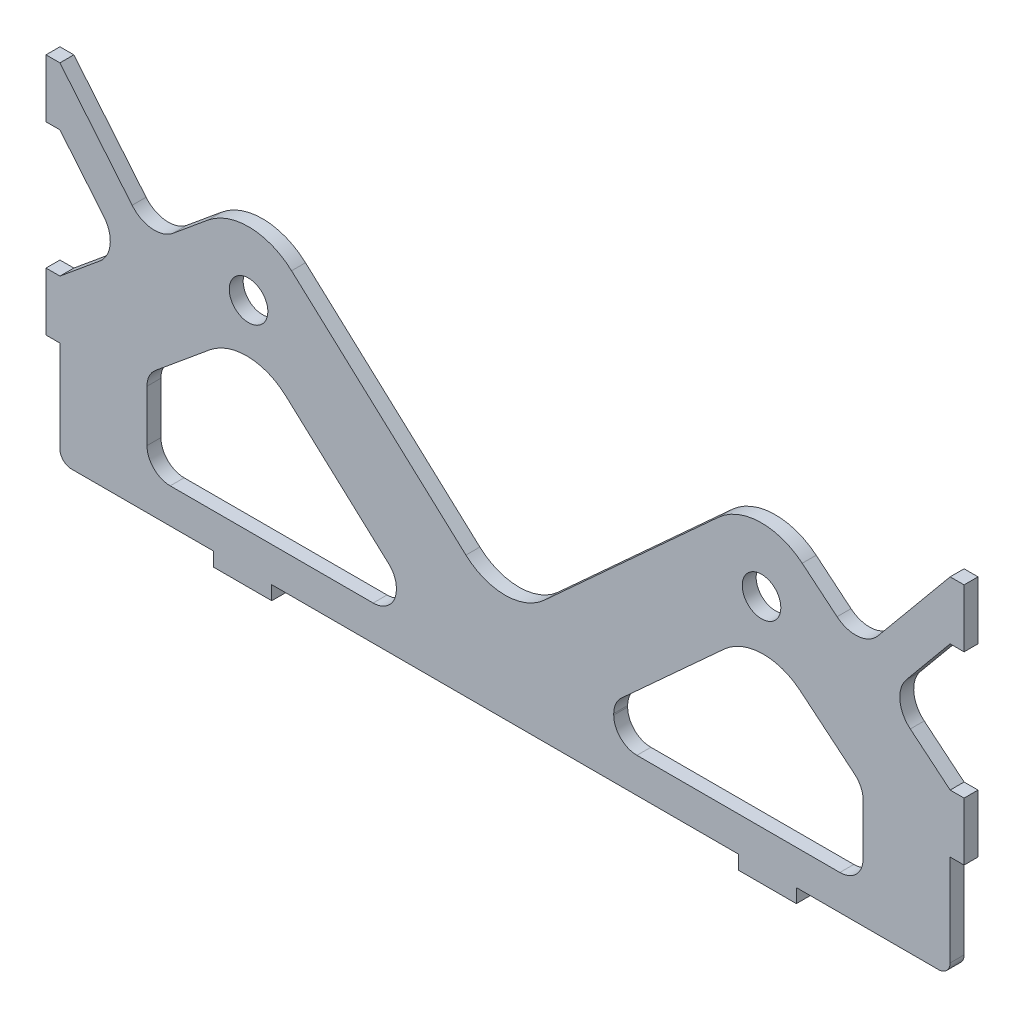
SolidWorks part; units mm, degrees
material "AISI 1020"
ref_plane "Front Plane" through (0, 0, 0) normal (0, 0, 1) x (1, 0, 0)
ref_plane "Top Plane" through (0, 0, 0) normal (0, 1, 0) x (1, 0, 0)
ref_plane "Right Plane" through (0, 0, 0) normal (1, 0, 0) x (0, 0, -1)
sketch "Sketch1" plane through (0, 0, 0) normal (0, 0, 1) x (1, 0, 0)
  line L1 (-97.4016, 35.56) -> (-97.4016, 62.7603) construction
  line L5 (51.054, 0) -> (-51.054, 0)
  line L6 (-51.054, 0) -> (-51.054, -3.048)
  line L7 (-51.054, -3.048) -> (-63.754, -3.048)
  line L8 (-63.754, -3.048) -> (-63.754, 0)
  line L9 (-63.754, 0) -> (-94.8616, 0)
  line L10 (-97.4016, 2.54) -> (-97.4016, 22.606)
  line L11 (-97.4016, 22.606) -> (-100.4496, 22.606)
  line L12 (-100.4496, 22.606) -> (-100.4496, 35.306)
  line L13 (-100.4496, 35.306) -> (-97.4016, 35.306)
  line L15 (-100.4496, 35.56) -> (-100.4496, 62.7603) construction
  line L16 (-64.008, -3.048) -> (-94.7346, -3.048) construction
  line L17 (-97.4016, 35.306) -> (-65.0347, 62.0991)
  line L18 (-46.712, 61.6589) -> (0, 19.05)
  line L19 (-100.4496, 35.56) -> (-97.4016, 35.56) construction
  line L20 (-50.8, -3.048) -> (-50.8, 0) construction
  line L21 (-97.4016, 2.667) -> (-97.4016, 22.352) construction
  line L22 (0, -1000) -> (0, 49000) construction
  line L23 (46.712, 61.6589) -> (0, 19.05)
  line L24 (97.4016, 35.306) -> (65.0347, 62.0991)
  line L25 (100.4496, 35.306) -> (97.4016, 35.306)
  line L26 (100.4496, 22.606) -> (100.4496, 35.306)
  line L27 (97.4016, 22.606) -> (100.4496, 22.606)
  line L28 (97.4016, 2.54) -> (97.4016, 22.606)
  line L29 (63.754, 0) -> (94.8616, 0)
  line L30 (63.754, -3.048) -> (63.754, 0)
  line L31 (51.054, -3.048) -> (63.754, -3.048)
  line L32 (51.054, 0) -> (51.054, -3.048)
  arc A0 (-46.712, 61.6589) -> (-65.0347, 62.0991) centre (-56.1266, 51.3377) ccw
  arc A1 (-94.8616, 0) -> (-97.4016, 2.54) centre (-94.8616, 2.54) cw
  circle A2 centre (56.1266, 51.3377) radius 4.2227
  circle A3 centre (-56.1266, 51.3377) radius 4.2227
  circle A4 centre (-56.1266, 51.3377) radius 4.2227
  arc A5 (94.8616, 0) -> (97.4016, 2.54) centre (94.8616, 2.54) ccw
  arc A6 (46.712, 61.6589) -> (65.0347, 62.0991) centre (56.1266, 51.3377) cw
  point P52 (0, 0)
  dimension "D2" = 27.94
  dimension "D7" = 2.54
  dimension "D1" = 12.7
  dimension "D4" = 19.05
  dimension "D5" = 0.254
  dimension "D6" = 0.254
  dimension "D3" = 0.254
extrude "Boss-Extrude1" add sketch "Sketch1" against normal blind 3.048 contours A2 | A4 | L17 A0 L18 L23 A6 L24 L25 L26 L27 L28 A5 L29 L30 L31 L32 L5 L6 L7 L8 L9 A1 L10 L11 L12 L13
fillet "Fillet1" radius 12.7 1 edges at (0, 19.05, -1.524)
sketch "Sketch3" plane through (0, 0, 0) normal (0, 0, 1) x (1, 0, 0)
  line L0 (-64.629, 37.7048) -> (-78.3516, 26.3453)
  line L1 (-78.3516, 26.3453) -> (-78.3516, 7.62)
  line L2 (-78.3516, 7.62) -> (-23.7825, 7.62)
  line L3 (-23.7825, 7.62) -> (-23.7825, 15.24)
  line L4 (-23.7825, 15.24) -> (-47.972, 37.3047)
  line L5 (-97.4016, 35.306) -> (-65.0347, 62.0991) construction
  line L6 (-46.712, 61.6589) -> (-8.5587, 26.8569) construction
  line L7 (-97.4016, 2.54) -> (-97.4016, 22.606) construction
  line L8 (51.054, 0) -> (-51.054, 0) construction
  arc A0 (-64.629, 37.7048) -> (-47.972, 37.3047) centre (-56.5307, 27.9218) cw
  point P17 (-56.1266, 44.743)
  dimension "D4" = 12.7
  dimension "D1" = 19.05
  dimension "D2" = 19.05
  dimension "D3" = 7.62
  dimension "D5" = 7.62
extrude "Cut-Extrude1" cut sketch "Sketch3" against normal through all both and the other way through all
fillet "Fillet2" radius 5.08 4 edges at (-78.3516, 7.62, -1.524) (-23.7825, 7.62, -1.524) (-23.7825, 15.24, -1.524) (-78.3516, 26.3453, -1.524)
mirror "Mirror1" about plane through (0, 0, 0) normal (1, 0, 0) of "Fillet2", "Cut-Extrude1"
sketch "Sketch4" plane through (0, 0, 0) normal (0, 0, 1) x (1, 0, 0)
  line L0 (-97.4016, 75.7143) -> (-77.553, 51.7366)
  line L1 (-100.4496, 75.7143) -> (-97.4016, 75.7143)
  line L2 (-100.4496, 75.7143) -> (-100.4496, 63.0143)
  line L3 (-100.4496, 63.0143) -> (-97.4016, 63.0143)
  line L5 (-97.4016, 35.306) -> (-65.0347, 62.0991) construction
  line L6 (-97.4016, 63.0143) -> (-83.7912, 46.5726)
  line L7 (-83.7912, 46.5726) -> (-77.553, 51.7366)
  line L8 (-97.4016, 75.9683) -> (-100.4496, 75.9683) construction
  line L9 (-100.4496, 75.9683) -> (-100.4496, 104.9243) construction
  point P6 (-94.3757, 75.7143)
  point P13 (-96.7247, 63.0143)
  dimension "D1" = 12.7
  dimension "D2" = 0.254
extrude "Boss-Extrude2" add sketch "Sketch4" against normal up to surface (3.048 mm away) up to face at (60.3494, 51.3377, -3.048)
mirror "Mirror3" about plane through (0, 0, 0) normal (1, 0, 0) of "Boss-Extrude2"
fillet "Fillet4" radius 6.35 4 edges at (83.7912, 46.5726, -1.524) (77.553, 51.7366, -1.524) (-77.553, 51.7366, -1.524) (-83.7912, 46.5726, -1.524)
equation "\"D2@Sketch3\"=\"D1@Sketch3\""
